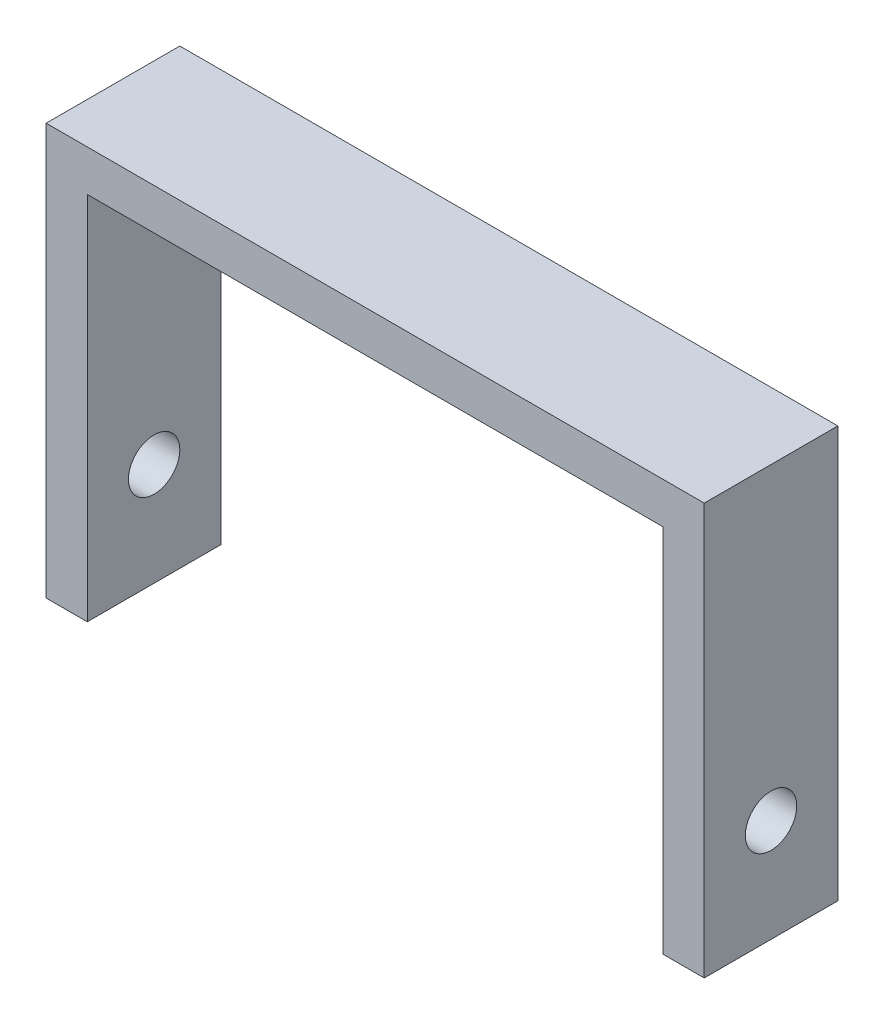
SolidWorks part; units mm, degrees
ref_plane "Plan de face" through (0, 0, 0) normal (0, 0, 1) x (1, 0, 0)
ref_plane "Plan de dessus" through (0, 0, 0) normal (0, 1, 0) x (1, 0, 0)
ref_plane "Plan de droite" through (0, 0, 0) normal (1, 0, 0) x (0, 0, -1)
sketch "Esquisse1" plane through (0, 0, 0) normal (0, 0, 1) x (1, 0, 0)
  line L0 (0, 0) -> (0, 40)
  line L1 (0, 40) -> (64, 40)
  line L2 (64, 40) -> (64, 0)
  line L3 (64, 0) -> (60, 0)
  line L4 (60, 0) -> (60, 36)
  line L5 (60, 36) -> (4, 36)
  line L6 (4, 36) -> (4, 0)
  line L7 (4, 0) -> (0, 0)
  dimension "D1" = 56
  dimension "D2" = 4
  dimension "D3" = 4
  dimension "D4" = 4
  dimension "D5" = 40
extrude "Boss.-Extru.1" add sketch "Esquisse1" along normal blind 13
sketch "Esquisse2" plane through (64, 0, 0) normal (1, 0, 0) x (0, 0, -1)
  line L0 (-6.5, 0) -> (-6.5, 40.9825) construction
  line L1 (-13, 0) -> (0, 0) construction
  line L2 (-6.5, 40.9825) -> (-13, 10) construction
  line L3 (-13, 0) -> (-13, 40) construction
  line L4 (-13, 10) -> (0, 10) construction
  line L5 (0, 0) -> (0, 40) construction
  line L6 (-13, 40) -> (0, 40) construction
  circle A0 centre (-6.5, 10) radius 2.5
  dimension "D2" = 5
  dimension "D1" = 30
extrude "Enlèv. mat.-Extru.1" cut sketch "Esquisse2" against normal through all
